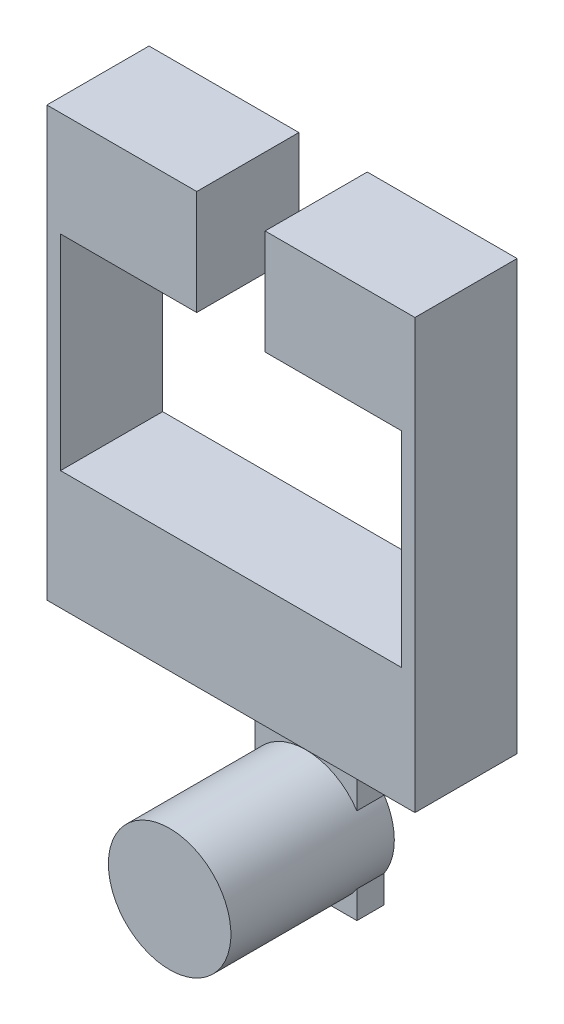
SolidWorks part; units mm, degrees
material "FEA Aluminum"
ref_plane "Front Plane" through (0, 0, 0) normal (0, 0, 1) x (1, 0, 0)
ref_plane "Top Plane" through (0, 0, 0) normal (0, 1, 0) x (1, 0, 0)
ref_plane "Right Plane" through (0, 0, 0) normal (1, 0, 0) x (0, 0, -1)
sketch "Sketch1" plane through (0, 0, 0) normal (0, 0, 1) x (1, 0, 0)
  line L1 (-34.3205, 79.975) -> (34.3205, 79.975)
  line L2 (-34.3205, 79.975) -> (-34.3205, 0)
  line L3 (-34.3205, 0) -> (34.3205, 0)
  line L4 (34.3205, 79.975) -> (34.3205, 0)
  dimension "D1" = 68.641
  dimension "D2" = 79.975
extrude "Main-Body" add sketch "Sketch1" along normal mid plane 19.05
sketch "Sketch2" plane through (0, 0, 9.525) normal (0, 0, 1) x (1, 0, 0)
  line L0 (0, 84.5954) -> (0, -7.8995) construction
  line L1 (-34.3205, 0) -> (34.3205, 0) construction
  line L2 (-31.7805, 60.417) -> (31.7805, 60.417)
  line L3 (-31.7805, 60.417) -> (-31.7805, 22.19)
  line L4 (-31.7805, 22.19) -> (31.7805, 22.19)
  line L5 (31.7805, 60.417) -> (31.7805, 22.19)
  point P7 (0, 0)
  point P8 (0, 0)
  dimension "D1" = 63.561
  dimension "D2" = 38.227
  dimension "D3" = 22.19
extrude "Lower-T-Cavity" cut sketch "Sketch2" against normal through all
sketch "Sketch3" plane through (0, 0, 9.525) normal (0, 0, 1) x (1, 0, 0)
  line L0 (0, 84.1431) -> (0, -5.638) construction
  line L1 (31.7805, 60.417) -> (-31.7805, 60.417) construction
  line L2 (-6.3754, 79.975) -> (6.3754, 79.975)
  line L3 (-6.3754, 79.975) -> (-6.3754, 60.417)
  line L4 (-6.3754, 60.417) -> (6.3754, 60.417)
  line L5 (6.3754, 79.975) -> (6.3754, 60.417)
  line L6 (34.3205, 79.975) -> (-34.3205, 79.975) construction
  point P7 (0, 0)
  dimension "D1" = 12.7508
extrude "Top-Slot" cut sketch "Sketch3" against normal through all
sketch "Sketch4" plane through (0, 0, -9.525) normal (0, 0, -1) x (-1, 0, 0)
  line L0 (0, 84.5954) -> (0, -5.9773) construction
  line L1 (34.3205, 0) -> (-34.3205, 0) construction
  line L2 (-9.525, 0) -> (9.525, 0)
  line L3 (-9.525, 0) -> (-9.525, -36.8237)
  line L4 (-9.525, -36.8237) -> (9.525, -36.8236)
  line L5 (9.525, 0) -> (9.525, -36.8236)
  point P9 (0, 0)
  dimension "D1" = 19.05
  dimension "D2" = 36.8236
extrude "Hanger" add sketch "Sketch4" against normal blind 5.08
sketch "Sketch5" plane through (0, 0, -9.525) normal (0, 0, -1) x (-1, 0, 0)
  circle A0 centre (0, -25.4) radius 11.4236
  point P2 (0, 0)
  point P3 (0, 0)
  dimension "D2" = 22.8473
  dimension "D1" = 25.4
extrude "Strap-Pin" add sketch "Sketch5" against normal blind 30.48
equation "\"Bracket_depth\" = 0.750in"
equation "\"Pin_diameter\" = 0.8995in"
equation "\"Pin_free_length\" = 1.000in"
equation "\"Hanger_width\" = 0.750in"
equation "\"Hanger_thickness\" = 0.2000in"
equation "\"Hanger_length\" = 1.000in"
equation "\"Web_thickness\" = 0.100in"
equation "\"Lip_height\" = 0.770in"
equation "\"Top_slot_width\" = 0.5020in"
equation "\"T_cavity_width\" = 2.5024in"
equation "\"T_cavity_height\"= 1.5050in"
equation "\"Crossmember_height\" = ( 3 * 1400 * 2.6024 / ( 2 * 0.75 * 10000 ) ) ^ ( 1 / 2 ) * 1in + 0.020in"
equation "\"D1@Sketch1\"=\"T_cavity_width\"+2*\"Web_thickness\""
equation "\"D2@Sketch1\"=\"Crossmember_height\"+\"T_cavity_height\"+\"Lip_height\""
equation "\"D1@Main-Body\" = \"Bracket_depth\""
equation "\"D1@Sketch2\"=\"T_cavity_width\""
equation "\"D2@Sketch2\"=\"T_cavity_height\""
equation "\"D3@Sketch2\"=\"Crossmember_height\""
equation "\"D1@Sketch3\"=\"Top_slot_width\""
equation "\"D1@Sketch4\"=\"Hanger_width\""
equation "\"D2@Sketch4\"=\"Hanger_length\"+\"Pin_diameter\"/2"
equation "\"D1@Hanger\" = \"Hanger_thickness\""
equation "\"D1@Sketch5\"=\"Hanger_length\""
equation "\"D2@Sketch5\"=\"Pin_diameter\""
equation "\"D1@Strap-Pin\" = \"Pin_free_length\" + \"Hanger_thickness\""
